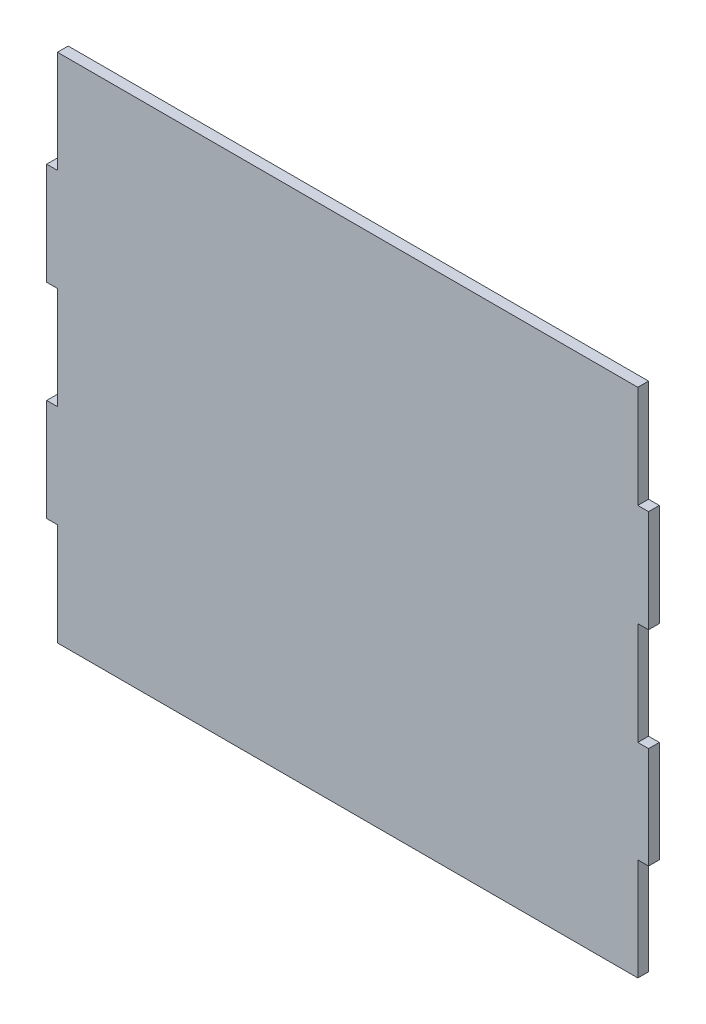
SolidWorks part; units mm, degrees
ref_plane "Plan de face" through (0, 0, 0) normal (0, 0, 1) x (1, 0, 0)
ref_plane "Plan de dessus" through (0, 0, 0) normal (0, 1, 0) x (1, 0, 0)
ref_plane "Plan de droite" through (0, 0, 0) normal (1, 0, 0) x (0, 0, -1)
sketch "Esquisse1" plane through (0, 0, 0) normal (0, 0, 1) x (1, 0, 0)
  line L0 (275, 238) -> (5, 238)
  line L1 (0, 190.4) -> (0, 142.8)
  line L2 (5, 0) -> (275, 0)
  line L3 (280, 47.6) -> (280, 94.9184)
  line L4 (280, 142.8) -> (280, 190.4)
  line L5 (0, 95.2) -> (0, 47.6)
  line L7 (280, 190.4) -> (275, 190.4)
  line L8 (275, 238) -> (275, 190.4)
  line L9 (280, 142.8) -> (275, 142.8)
  line L11 (280, 94.9184) -> (275, 94.9184)
  line L12 (275, 142.8) -> (275, 94.9184)
  line L15 (0, 190.4) -> (5, 190.4)
  line L16 (5, 238) -> (5, 190.4)
  line L17 (0, 142.8) -> (5, 142.8)
  line L19 (0, 95.2) -> (5, 95.2)
  line L20 (5, 142.8) -> (5, 95.2)
  line L21 (280, 47.6) -> (275, 47.6)
  line L24 (275, 47.6) -> (275, 0)
  line L25 (0, 47.6) -> (5, 47.6)
  line L28 (5, 47.6) -> (5, 0)
extrude "Boss.-Extru.1" add sketch "Esquisse1" along normal blind 5
